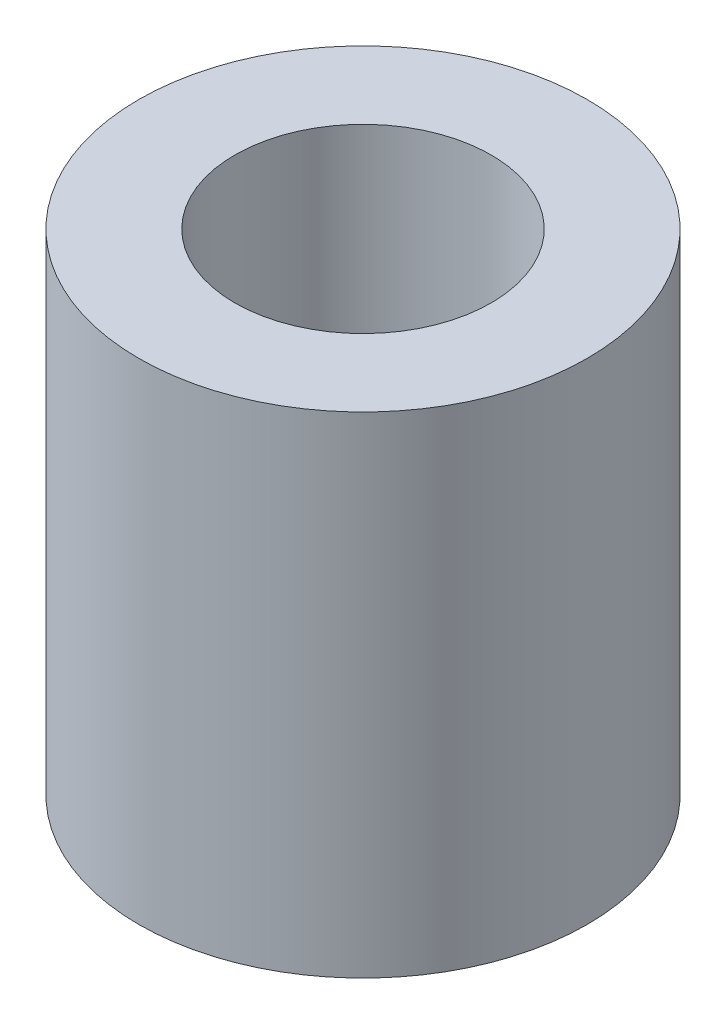
SolidWorks part; units mm, degrees
ref_plane "Front" through (0, 0, 0) normal (0, 0, 1) x (1, 0, 0)
ref_plane "Top" through (0, 0, 0) normal (0, 1, 0) x (1, 0, 0)
ref_plane "Right" through (0, 0, 0) normal (1, 0, 0) x (0, 0, -1)
sketch "Sketch2" plane through (0, 0, 0) normal (0, 1, 0) x (1, 0, 0)
  circle A0 centre (0, 0) radius 5.335
  circle A1 centre (0, 0) radius 3.05
  dimension "D1" = 10.67
  dimension "D2" = 6.1
extrude "Boss-Extrude1" add sketch "Sketch2" along normal blind 11.666
